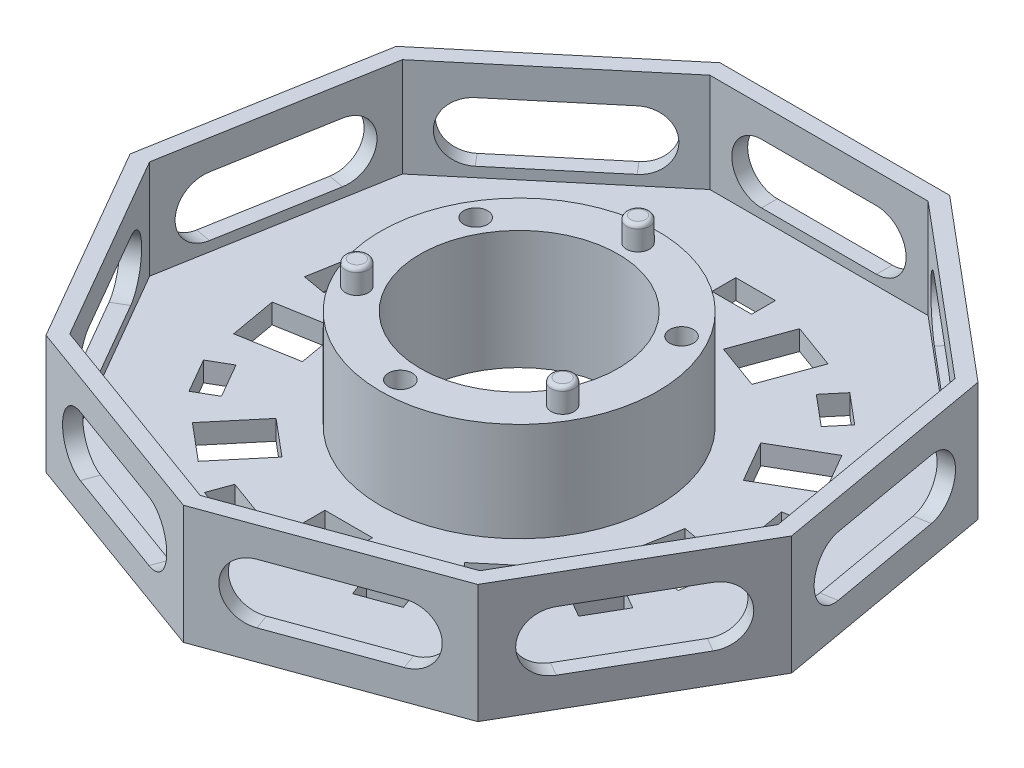
SolidWorks part; units mm, degrees
material "ABS"
ref_plane "Plano frontal" through (0, 0, 0) normal (0, 0, 1) x (1, 0, 0)
ref_plane "Plano superior" through (0, 0, 0) normal (0, 1, 0) x (1, 0, 0)
ref_plane "Plano direito" through (0, 0, 0) normal (1, 0, 0) x (0, 0, -1)
sketch "Esboço1" plane through (0, 0, 0) normal (0, 1, 0) x (1, 0, 0)
  line L0 (-1930.8999, 0) -> (1901.5326, 0) construction
  line L1 (-1218.0082, 1040.0915) -> (-51.2153, 61.036) construction
  line L2 (-51.2153, 61.036) -> (-812.7852, 1380.1139) construction
  line L3 (-812.7852, 1380.1139) -> (-1218.0082, 1040.0915) construction
  line L4 (-264.4905, 1579.6768) -> (0, 79.6768) construction
  line L5 (0, 79.6768) -> (264.4905, 1579.6768) construction
  line L6 (0, 0) -> (0, -1288.4902) construction
  line L7 (0, 0) -> (-78.4664, 13.8357) construction
  line L8 (-78.4664, 13.8357) -> (-1509.7497, 534.7803) construction
  line L9 (-1509.7497, 534.7803) -> (-1601.6063, 13.8357) construction
  line L10 (-1601.6063, 13.8357) -> (-78.4664, 13.8357) construction
  line L11 (-78.4664, 13.8357) -> (-1555.678, 274.308) construction
  line L12 (264.4905, 1579.6768) -> (-264.4905, 1579.6768) construction
  line L13 (812.7852, 1380.1139) -> (51.2153, 61.036) construction
  line L14 (51.2153, 61.036) -> (1218.0082, 1040.0915) construction
  line L15 (1218.0082, 1040.0915) -> (812.7852, 1380.1139) construction
  line L16 (1509.7497, 534.7803) -> (78.4664, 13.8357) construction
  line L17 (78.4664, 13.8357) -> (1601.6063, 13.8357) construction
  line L18 (1601.6063, 13.8357) -> (1509.7497, 534.7803) construction
  line L19 (-73.4306, 42.3952) -> (-83.5022, -14.7237)
  line L20 (-73.4306, 42.3952) -> (-29, 79.6768)
  line L21 (-29, 79.6768) -> (29, 79.6768)
  line L22 (29, 79.6768) -> (73.4306, 42.3952)
  line L23 (73.4306, 42.3952) -> (83.5022, -14.7237)
  line L24 (-83.5022, -14.7237) -> (-54.5022, -64.9532)
  line L25 (-54.5022, -64.9532) -> (0, -84.7903)
  line L26 (0, -84.7903) -> (54.5022, -64.9532)
  line L27 (54.5022, -64.9532) -> (83.5022, -14.7237)
  circle A0 centre (0, 0) radius 79.6768 construction
  circle A1 centre (0, 0) radius 25
  circle A2 centre (0, 0) radius 25 construction
  point P26 (0, 0)
  point P39 (-69.0022, -39.8384)
  dimension "D6" = 58
  dimension "D1" = 1500
  dimension "D2" = 20
  dimension "D3" = 5
  dimension "D4" = 180
extrude "Ressalto-extrusão1" add sketch "Esboço1" along normal blind 30
sketch "Esboço2" plane through (0, 30, 0) normal (0, 1, 0) x (1, 0, 0)
  line L9 (-79.3101, -13.9845) -> (-51.766, -61.6923)
  line L10 (-79.3101, -13.9845) -> (-51.766, -61.6923)
  line L11 (-51.766, -61.6923) -> (0, -80.5336)
  line L12 (-51.766, -61.6923) -> (0, -80.5336)
  line L13 (0, -80.5336) -> (51.766, -61.6923)
  line L14 (0, -80.5336) -> (51.766, -61.6923)
  line L15 (-27.5441, 75.6768) -> (-69.7442, 40.2668)
  line L16 (-69.7442, 40.2668) -> (-79.3101, -13.9845)
  line L17 (79.3101, -13.9845) -> (69.7442, 40.2668)
  line L18 (69.7442, 40.2668) -> (27.5441, 75.6768)
  line L19 (27.5441, 75.6768) -> (-27.5441, 75.6768)
  line L20 (-27.5441, 75.6768) -> (-69.7442, 40.2668)
  line L21 (-69.7442, 40.2668) -> (-79.3101, -13.9845)
  line L22 (79.3101, -13.9845) -> (69.7442, 40.2668)
  line L23 (69.7442, 40.2668) -> (27.5441, 75.6768)
  line L24 (27.5441, 75.6768) -> (-27.5441, 75.6768)
  line L25 (51.766, -61.6923) -> (79.3101, -13.9845)
  line L26 (51.766, -61.6923) -> (79.3101, -13.9845)
  circle A2 centre (0, 0) radius 35
  circle A5 centre (0, 0) radius 25 construction
  dimension "D2" = 10
  dimension "D1" = 4
extrude "Corte-extrusão1" cut sketch "Esboço2" against normal offset from surface (25 mm away) 5 up to face at (0, 0, 0)
sketch "Esboço3" plane through (0, 30, 0) normal (0, 1, 0) x (1, 0, 0)
  line L0 (0, 25) -> (0, 35) construction
  line L1 (21.6506, -12.5) -> (30.3109, -17.5) construction
  line L2 (-21.6506, -12.5) -> (-30.3109, -17.5) construction
  circle A0 centre (0, 30) radius 2.9
  circle A1 centre (25.9808, -15) radius 2.9
  circle A2 centre (0, 0) radius 25 construction
  circle A3 centre (0, 0) radius 35 construction
  circle A4 centre (-25.9808, -15) radius 2.9
  point P10 (77.7531, 51.461)
  point P21 (0, 0)
  point P30 (0, 0)
  dimension "D1" = 5.8
  dimension "D2" = 3
extrude "Ressalto-extrusão2" add sketch "Esboço3" along normal blind 6
sketch "Esboço4" plane through (0, 30, 0) normal (0, 1, 0) x (1, 0, 0)
  line L0 (0, -25) -> (0, -35) construction
  line L1 (-21.6506, 12.5) -> (-30.3109, 17.5) construction
  line L2 (21.6506, 12.5) -> (30.3109, 17.5) construction
  circle A0 centre (0, 0) radius 25 construction
  circle A1 centre (0, 0) radius 35 construction
  circle A2 centre (0, -30) radius 3
  circle A3 centre (-25.9808, 15) radius 3
  circle A4 centre (25.9808, 15) radius 3
  point P20 (0, 0)
  dimension "D1" = 6
extrude "Corte-extrusão2" cut sketch "Esboço4" against normal through all
sketch "Esboço5" plane through (0, 0, -79.6768) normal (0, 0, -1) x (-1, 0, 0)
  line L0 (0, 0) -> (0, 30) construction
  line L2 (-14.5, 15) -> (14.5, 15) construction
  line L3 (-14.5, 22.5) -> (14.5, 22.5)
  line L4 (-14.5, 7.5) -> (14.5, 7.5)
  line L5 (-29, 30) -> (29, 30) construction
  arc A0 (-14.5, 22.5) -> (-14.5, 7.5) centre (-14.5, 15) ccw
  arc A1 (14.5, 7.5) -> (14.5, 22.5) centre (14.5, 15) ccw
  point P7 (0, 15)
  dimension "D2" = 7.5
  dimension "D1" = 29
extrude "Corte-extrusão3" cut sketch "Esboço5" against normal up to next
sketch "Esboço6" plane through (0, 0, 0) normal (0, 0, 1) x (1, 0, 0)
  line L0 (0, 0) -> (0, 57.3938) construction
pattern_circular "PadrãoCircular1" count 9 over 360 about axis through (0, 0, 0) along (0, 1, 0) of "Corte-extrusão3"
sketch "Esboço7" plane through (0, 5, 0) normal (0, 1, 0) x (1, 0, 0)
  line L0 (0, 75.6768) -> (0, 0) construction
  line L1 (27.5441, 75.6768) -> (-27.5441, 75.6768) construction
  line L2 (30.6726, 44.3328) -> (38.333, 37.9049)
  line L3 (-5, 53.6768) -> (5, 53.6768)
  line L4 (-5, 53.6768) -> (-5, 59.6768)
  line L5 (-5, 59.6768) -> (5, 59.6768)
  line L6 (5, 53.6768) -> (5, 59.6768)
  line L7 (-5, 53.6768) -> (5, 59.6768) construction
  line L8 (-5, 59.6768) -> (5, 53.6768) construction
  line L9 (30.6726, 44.3328) -> (34.5293, 48.9291)
  line L10 (34.5293, 48.9291) -> (42.1898, 42.5012)
  line L11 (38.333, 37.9049) -> (42.1898, 42.5012)
  line L12 (48.6441, 57.9718) -> (0, 0) construction
  line L13 (30.6726, 44.3328) -> (42.1898, 42.5012) construction
  line L14 (34.5293, 48.9291) -> (38.333, 37.9049) construction
  line L15 (51.9931, 14.2449) -> (53.7296, 4.3968)
  line L16 (51.9931, 14.2449) -> (57.902, 15.2868)
  line L17 (57.902, 15.2868) -> (59.6385, 5.4387)
  line L18 (53.7296, 4.3968) -> (59.6385, 5.4387)
  line L19 (74.5271, 13.1411) -> (0, 0) construction
  line L20 (51.9931, 14.2449) -> (59.6385, 5.4387) construction
  line L21 (57.902, 15.2868) -> (53.7296, 4.3968) construction
  line L22 (48.9855, -22.5083) -> (43.9855, -31.1685)
  line L23 (48.9855, -22.5083) -> (54.1817, -25.5083)
  line L24 (54.1817, -25.5083) -> (49.1817, -34.1685)
  line L25 (43.9855, -31.1685) -> (49.1817, -34.1685)
  line L26 (65.5381, -37.8384) -> (0, 0) construction
  line L27 (48.9855, -22.5083) -> (49.1817, -34.1685) construction
  line L28 (54.1817, -25.5083) -> (43.9855, -31.1685) construction
  line L29 (23.057, -48.7296) -> (13.6601, -52.1498)
  line L30 (23.057, -48.7296) -> (25.1091, -54.3678)
  line L31 (25.1091, -54.3678) -> (15.7122, -57.788)
  line L32 (13.6601, -52.1498) -> (15.7122, -57.788)
  line L33 (25.883, -71.113) -> (0, 0) construction
  line L34 (23.057, -48.7296) -> (15.7122, -57.788) construction
  line L35 (25.1091, -54.3678) -> (13.6601, -52.1498) construction
  line L36 (-13.6601, -52.1498) -> (-23.057, -48.7296)
  line L37 (-13.6601, -52.1498) -> (-15.7122, -57.788)
  line L38 (-15.7122, -57.788) -> (-25.1091, -54.3678)
  line L39 (-23.057, -48.7296) -> (-25.1091, -54.3678)
  line L40 (-25.883, -71.113) -> (0, 0) construction
  line L41 (-13.6601, -52.1498) -> (-25.1091, -54.3678) construction
  line L42 (-15.7122, -57.788) -> (-23.057, -48.7296) construction
  line L43 (-43.9855, -31.1685) -> (-48.9855, -22.5083)
  line L44 (-43.9855, -31.1685) -> (-49.1817, -34.1685)
  line L45 (-49.1817, -34.1685) -> (-54.1817, -25.5083)
  line L46 (-48.9855, -22.5083) -> (-54.1817, -25.5083)
  line L47 (-65.5381, -37.8384) -> (0, 0) construction
  line L48 (-43.9855, -31.1685) -> (-54.1817, -25.5083) construction
  line L49 (-49.1817, -34.1685) -> (-48.9855, -22.5083) construction
  line L50 (-53.7296, 4.3968) -> (-51.9931, 14.2449)
  line L51 (-53.7296, 4.3968) -> (-59.6385, 5.4387)
  line L52 (-59.6385, 5.4387) -> (-57.902, 15.2868)
  line L53 (-51.9931, 14.2449) -> (-57.902, 15.2868)
  line L54 (-74.5271, 13.1411) -> (0, 0) construction
  line L55 (-53.7296, 4.3968) -> (-57.902, 15.2868) construction
  line L56 (-59.6385, 5.4387) -> (-51.9931, 14.2449) construction
  line L57 (-38.333, 37.9049) -> (-30.6726, 44.3328)
  line L58 (-38.333, 37.9049) -> (-42.1898, 42.5012)
  line L59 (-42.1898, 42.5012) -> (-34.5293, 48.9291)
  line L60 (-30.6726, 44.3328) -> (-34.5293, 48.9291)
  line L61 (-48.6441, 57.9718) -> (0, 0) construction
  line L62 (-38.333, 37.9049) -> (-34.5293, 48.9291) construction
  line L63 (-42.1898, 42.5012) -> (-30.6726, 44.3328) construction
  line L64 (0, 0) -> (0, -80.5336) construction
  line L65 (-23.0652, -36.8224) -> (-32.2577, -29.1089)
  line L66 (6, -43.0336) -> (-6, -43.0336)
  line L67 (6, -43.0336) -> (6, -58.0336)
  line L68 (6, -58.0336) -> (-6, -58.0336)
  line L69 (-6, -43.0336) -> (-6, -58.0336)
  line L70 (6, -43.0336) -> (-6, -58.0336) construction
  line L71 (6, -58.0336) -> (-6, -43.0336) construction
  line L72 (-23.0652, -36.8224) -> (-32.707, -48.3131)
  line L73 (-32.707, -48.3131) -> (-41.8996, -40.5996)
  line L74 (-32.2577, -29.1089) -> (-41.8996, -40.5996)
  line L75 (-23.0652, -36.8224) -> (-41.8996, -40.5996) construction
  line L76 (-32.707, -48.3131) -> (-32.2577, -29.1089) construction
  line L77 (0, 0) -> (-51.766, -61.6923) construction
  line L78 (-41.338, -13.3816) -> (-43.4217, -1.5639)
  line L79 (-41.338, -13.3816) -> (-56.1101, -15.9863)
  line L80 (-56.1101, -15.9863) -> (-58.1938, -4.1686)
  line L81 (-43.4217, -1.5639) -> (-58.1938, -4.1686)
  line L82 (-41.338, -13.3816) -> (-58.1938, -4.1686) construction
  line L83 (-56.1101, -15.9863) -> (-43.4217, -1.5639) construction
  line L84 (0, 0) -> (-79.3101, -13.9845) construction
  line L85 (-40.2682, 16.3207) -> (-34.2682, 26.713)
  line L86 (-40.2682, 16.3207) -> (-53.2586, 23.8207)
  line L87 (-53.2586, 23.8207) -> (-47.2586, 34.213)
  line L88 (-34.2682, 26.713) -> (-47.2586, 34.213)
  line L89 (-40.2682, 16.3207) -> (-47.2586, 34.213) construction
  line L90 (-53.2586, 23.8207) -> (-34.2682, 26.713) construction
  line L91 (0, 0) -> (-69.7442, 40.2668) construction
  line L92 (-20.3565, 38.3863) -> (-9.0802, 42.4905)
  line L93 (-20.3565, 38.3863) -> (-25.4868, 52.4816)
  line L94 (-25.4868, 52.4816) -> (-14.2105, 56.5859)
  line L95 (-9.0802, 42.4905) -> (-14.2105, 56.5859)
  line L96 (-20.3565, 38.3863) -> (-14.2105, 56.5859) construction
  line L97 (-25.4868, 52.4816) -> (-9.0802, 42.4905) construction
  line L98 (0, 0) -> (-27.5441, 75.6768) construction
  line L99 (9.0802, 42.4905) -> (20.3565, 38.3863)
  line L100 (9.0802, 42.4905) -> (14.2105, 56.5859)
  line L101 (14.2105, 56.5859) -> (25.4868, 52.4816)
  line L102 (20.3565, 38.3863) -> (25.4868, 52.4816)
  line L103 (9.0802, 42.4905) -> (25.4868, 52.4816) construction
  line L104 (14.2105, 56.5859) -> (20.3565, 38.3863) construction
  line L105 (0, 0) -> (27.5441, 75.6768) construction
  line L106 (34.2682, 26.713) -> (40.2682, 16.3207)
  line L107 (34.2682, 26.713) -> (47.2586, 34.213)
  line L108 (47.2586, 34.213) -> (53.2586, 23.8207)
  line L109 (40.2682, 16.3207) -> (53.2586, 23.8207)
  line L110 (34.2682, 26.713) -> (53.2586, 23.8207) construction
  line L111 (47.2586, 34.213) -> (40.2682, 16.3207) construction
  line L112 (0, 0) -> (69.7442, 40.2668) construction
  line L113 (43.4217, -1.5639) -> (41.338, -13.3816)
  line L114 (43.4217, -1.5639) -> (58.1938, -4.1686)
  line L115 (58.1938, -4.1686) -> (56.1101, -15.9863)
  line L116 (41.338, -13.3816) -> (56.1101, -15.9863)
  line L117 (43.4217, -1.5639) -> (56.1101, -15.9863) construction
  line L118 (58.1938, -4.1686) -> (41.338, -13.3816) construction
  line L119 (0, 0) -> (79.3101, -13.9845) construction
  line L120 (32.2577, -29.1089) -> (23.0652, -36.8224)
  line L121 (32.2577, -29.1089) -> (41.8996, -40.5996)
  line L122 (41.8996, -40.5996) -> (32.707, -48.3131)
  line L123 (23.0652, -36.8224) -> (32.707, -48.3131)
  line L124 (32.2577, -29.1089) -> (32.707, -48.3131) construction
  line L125 (41.8996, -40.5996) -> (23.0652, -36.8224) construction
  line L126 (0, 0) -> (51.766, -61.6923) construction
  point P5 (0, 56.6768)
  point P10 (0, -50.5336)
  point P14 (36.4312, 43.417)
  point P20 (55.8158, 9.8418)
  point P26 (49.0836, -28.3384)
  point P32 (19.3846, -53.2588)
  point P38 (-19.3846, -53.2588)
  point P44 (-49.0836, -28.3384)
  point P50 (-55.8158, 9.8418)
  point P56 (-36.4312, 43.417)
  point P61 (0, 0)
  point P69 (-32.4824, -38.711)
  point P75 (-49.7659, -8.7751)
  point P81 (-43.7634, 25.2668)
  point P87 (-17.2835, 47.4861)
  point P93 (17.2835, 47.4861)
  point P99 (43.7634, 25.2668)
  point P105 (49.7659, -8.7751)
  point P111 (32.4824, -38.711)
  point P117 (0, 0)
  dimension "D1" = 6
  dimension "D2" = 10
  dimension "D3" = 16
  dimension "D4" = 12
  dimension "D5" = 15
  dimension "D6" = 30
  dimension "D7" = 9
extrude "Corte-extrusão4" cut sketch "Esboço7" against normal through all and the other way through all
fillet "Filete1" radius 1 3 edges at (0, 36, -27.1) (-25.9808, 36, 17.9) (25.9808, 36, 17.9)
